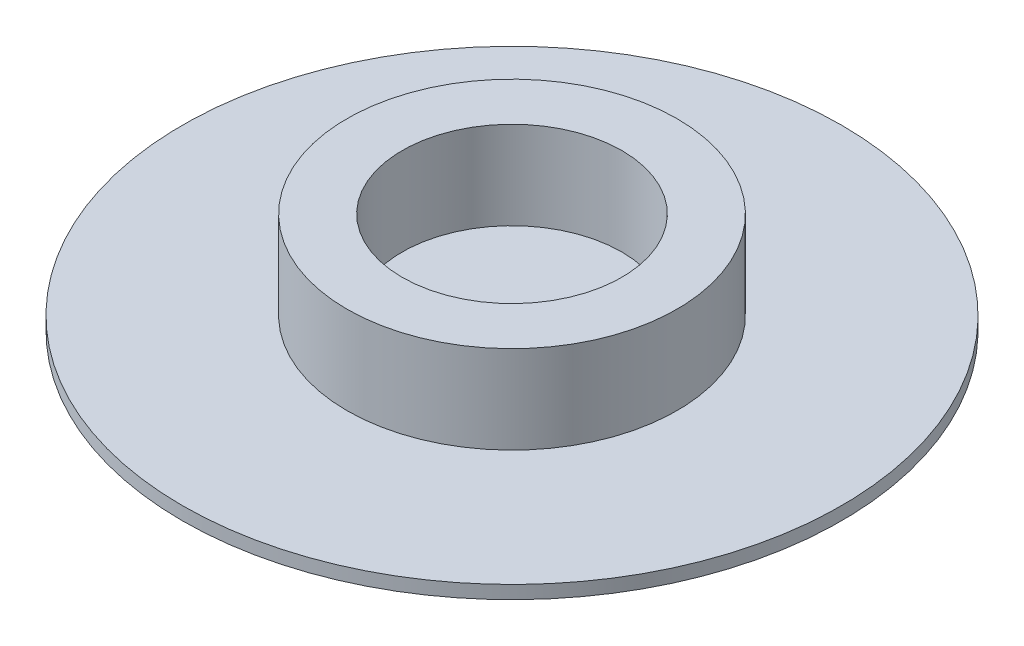
SolidWorks part; units mm, degrees
ref_plane "Front Plane" through (0, 0, 0) normal (0, 0, 1) x (1, 0, 0)
ref_plane "Top Plane" through (0, 0, 0) normal (0, 1, 0) x (1, 0, 0)
ref_plane "Right Plane" through (0, 0, 0) normal (1, 0, 0) x (0, 0, -1)
sketch "Sketch1" plane through (0, 0, 0) normal (0, 1, 0) x (1, 0, 0)
  circle A0 centre (0, 0) radius 75
  dimension "D1" = 150
extrude "Boss-Extrude1" add sketch "Sketch1" along normal blind 3
sketch "Sketch2" plane through (0, 0, 0) normal (0, -1, 0) x (1, 0, 0)
  line L0 (0, 42.0782) -> (0, -48.9017) construction
  line L1 (-47.5, -25) -> (-32.5, -25)
  line L2 (-47.5, -25) -> (-47.5, 25)
  line L3 (-47.5, 25) -> (-32.5, 25)
  line L4 (-32.5, -25) -> (-32.5, 25)
  line L5 (-47.5, -25) -> (-32.5, 25) construction
  line L6 (-47.5, 25) -> (-32.5, -25) construction
  line L7 (47.5, 25) -> (32.5, -25) construction
  line L8 (47.5, -25) -> (32.5, 25) construction
  line L9 (32.5, -25) -> (32.5, 25)
  line L10 (47.5, 25) -> (32.5, 25)
  line L11 (47.5, -25) -> (47.5, 25)
  line L12 (47.5, -25) -> (32.5, -25)
  point P0 (-40, 0)
  point P8 (0, 0)
  point P13 (40, 0)
  dimension "D1" = 50
  dimension "14" = 15
  dimension "D2" = 40
extrude "Dán Băng dính" cut sketch "Sketch2" against normal blind 1
sketch "Sketch3" plane through (0, 3, 0) normal (0, 1, 0) x (1, 0, 0)
  circle A0 centre (0, 0) radius 25
  circle A1 centre (0, 0) radius 37.5593
  dimension "D1" = 50
extrude "gắn vòng bi" add sketch "Sketch3" along normal blind 20
